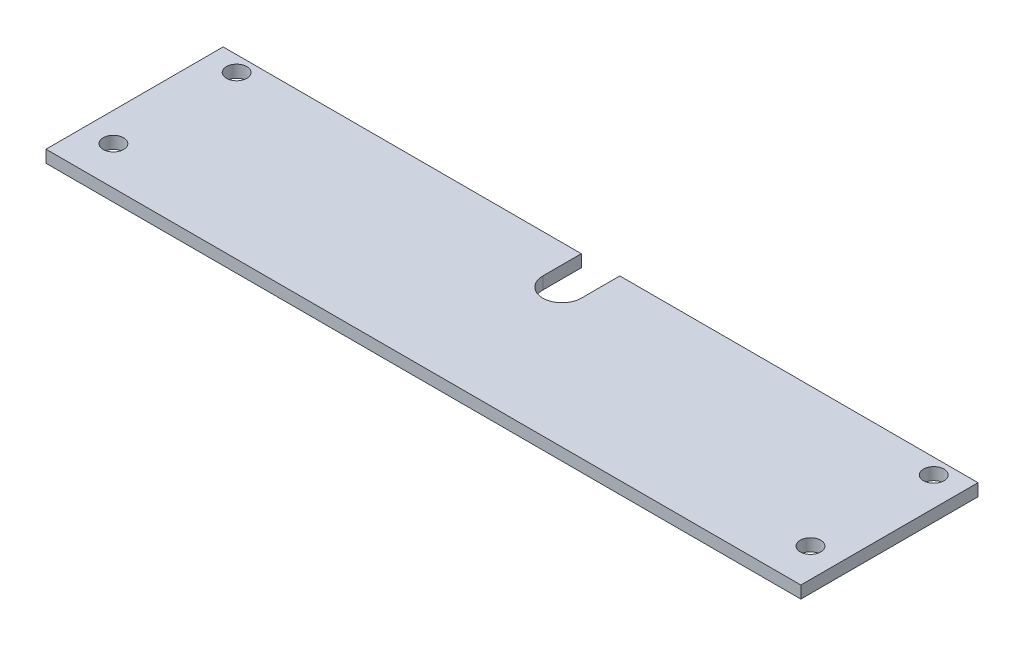
SolidWorks part; units mm, degrees
ref_plane "Front Plane" through (0, 0, 0) normal (0, 0, 1) x (1, 0, 0)
ref_plane "Top Plane" through (0, 0, 0) normal (0, 1, 0) x (1, 0, 0)
ref_plane "Right Plane" through (0, 0, 0) normal (1, 0, 0) x (0, 0, -1)
sketch "Sketch1" plane through (0, 0, 0) normal (0, 1, 0) x (1, 0, 0)
  line L1 (0, 0) -> (196, 0)
  line L2 (0, 0) -> (0, 46)
  line L3 (0, 46) -> (196, 46)
  line L4 (196, 0) -> (196, 46)
  dimension "D1" = 46
  dimension "D2" = 196
extrude "Boss-Extrude1" add sketch "Sketch1" along normal blind 3.175
sketch "Sketch2" plane through (0, 3.175, 0) normal (0, 1, 0) x (1, 0, 0)
  line L0 (103, 36) -> (93, 36) construction
  line L1 (196, 46) -> (0, 46) construction
  line L2 (98, 46) -> (98, 31) construction
  line L8 (93, 36) -> (93, 46)
  line L9 (93, 46) -> (103, 46)
  line L10 (103, 46) -> (103, 36)
  arc A6 (93, 36) -> (103, 36) centre (98, 36) ccw
  point P2 (98, 32.9451)
  point P15 (98, 36)
  dimension "D1" = 10
  dimension "D2" = 10
extrude "Cut-Extrude1" cut sketch "Sketch2" against normal blind 3.175
sketch "Sketch3" plane through (0, 3.175, 0) normal (0, 1, 0) x (1, 0, 0)
  line L0 (196, 0) -> (196, 46) construction
  line L1 (7.5, 36) -> (188.5, 36) construction
  line L2 (7.5, 36) -> (7.5, 10) construction
  line L3 (7.5, 10) -> (188.5, 10) construction
  line L4 (188.5, 36) -> (188.5, 10) construction
  line L5 (7.5, 36) -> (188.5, 10) construction
  line L6 (7.5, 10) -> (188.5, 36) construction
  line L7 (0, 0) -> (196, 0) construction
  line L8 (188.5, 36) -> (188.5, 42)
  line L10 (7.5, 36) -> (7.5, 42)
  line L11 (98, 46) -> (98, 0) construction
  line L14 (0, 23) -> (196, 23) construction
  line L15 (0, 46) -> (0, 0) construction
  line L16 (93, 46) -> (0, 46) construction
  line L17 (196, 46) -> (103, 46) construction
  point P1 (188.5, 10)
  point P2 (7.5, 36)
  point P3 (7.5, 10)
  point P13 (188.5, 42)
  point P18 (7.5, 42)
  point P31 (98, 23)
  dimension "D1" = 7.5
  dimension "D2" = 10
  dimension "D3" = 6
  dimension "D4" = 6
  dimension "D5" = 181
  dimension "D6" = 4
hole_wizard "M5 Clearance Hole1" positions "Sketch3" profile "Sketch4" hole size "M5" standard "ANSI Metric"
sketch "Sketch4" plane through (188.5, 3.175, -10) normal (1, 0, 0) x (0, 0, 1)
  line L0 (0, 0) -> (0, 3.175)
  line L1 (0, 3.175) -> (2.65, 3.175)
  line L2 (2.65, 3.175) -> (2.65, 0)
  line L5 (2.65, 0) -> (0, 0)
  line L11 (0, -6.35) -> (0, 107.95) construction
  dimension "Thru Hole Dia." = 5.3
  dimension "Thru Hole Depth" = 3.175
